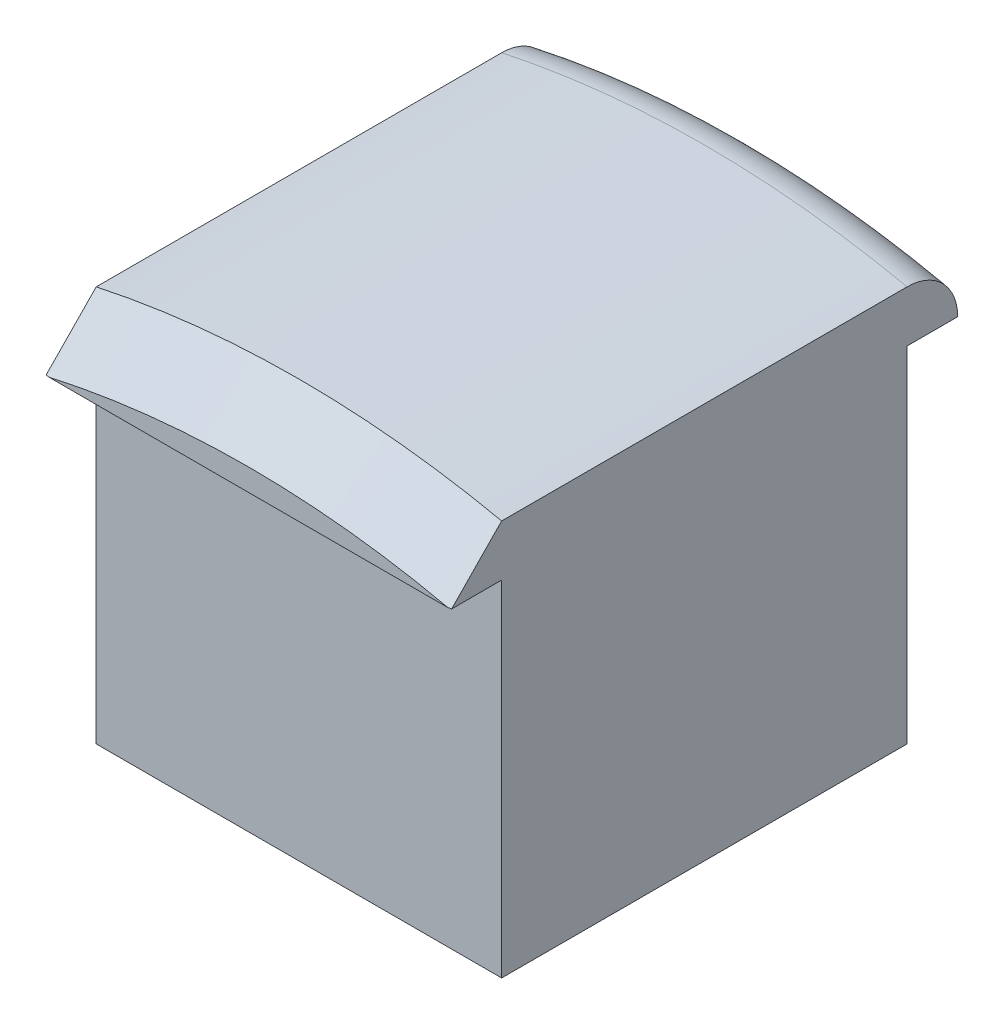
SolidWorks part; units mm, degrees
ref_plane "Alzado" through (0, 0, 0) normal (0, 0, 1) x (1, 0, 0)
ref_plane "Planta" through (0, 0, 0) normal (0, 1, 0) x (1, 0, 0)
ref_plane "Vista lateral" through (0, 0, 0) normal (1, 0, 0) x (0, 0, -1)
sketch "Croquis1" plane through (0, 0, 0) normal (0, 0, 1) x (1, 0, 0)
  line L9 (-50.7946, 110.0777) -> (-50.7946, 76.8462)
  line L10 (-50.7946, 76.8462) -> (-10.7946, 76.8462)
  line L11 (-10.7946, 76.8462) -> (-10.7946, 110.0777)
  line L14 (-50.7946, 110.0777) -> (-50.7946, 115.8971)
  line L15 (-10.7946, 110.0777) -> (-10.7946, 115.8971)
  arc A1 (-10.7946, 115.8971) -> (-50.7946, 115.8971) centre (-30.7946, 23.0262) ccw
  point P1 (-30.7946, 118.0262)
  dimension "D1" = 41.18
  dimension "D9" = 190
  dimension "D3" = 40
  dimension "D6" = 20
extrude "Saliente-Extruir1" add sketch "Croquis1" along normal blind 50
sketch "Croquis4" plane through (-50.7946, 0, 0) normal (-1, 0, 0) x (0, 0, 1)
  line L0 (0, 76.8462) -> (0, 115.8971) construction
  line L1 (0, 110.8462) -> (5, 110.8462)
  line L2 (0, 110.8462) -> (0, 76.8462)
  line L3 (0, 76.8462) -> (5, 76.8462)
  line L4 (5, 110.8462) -> (5, 76.8462)
  line L5 (50, 76.8462) -> (0, 76.8462) construction
  line L6 (50, 76.8462) -> (50, 115.8971) construction
  line L7 (50, 110.8462) -> (45, 110.8462)
  line L8 (50, 110.8462) -> (50, 76.8462)
  line L9 (50, 76.8462) -> (45, 76.8462)
  line L10 (45, 110.8462) -> (45, 76.8462)
  dimension "D1" = 5
  dimension "D2" = 5
  dimension "D3" = 34
  dimension "D4" = 34
extrude "Cortar-Extruir3" cut sketch "Croquis4" against normal blind 50
sketch "Croquis5" plane through (0, 0, 5) normal (0, 0, -1) x (-1, 0, 0)
  line L0 (10.7946, 110.8462) -> (50.7946, 110.8462) construction
  line L1 (12.7946, 110.8462) -> (48.7946, 110.8462)
  line L2 (12.7946, 110.8462) -> (12.7946, 78.8462)
  line L3 (12.7946, 78.8462) -> (48.7946, 78.8462)
  line L4 (48.7946, 110.8462) -> (48.7946, 78.8462)
  line L5 (10.7946, 76.8462) -> (10.7946, 110.8462) construction
  line L6 (50.7946, 76.8462) -> (50.7946, 110.8462) construction
  line L7 (10.7946, 76.8462) -> (50.7946, 76.8462) construction
  dimension "D1" = 2
  dimension "D2" = 2
  dimension "D3" = 2
extrude "Cortar-Extruir4" cut sketch "Croquis5" against normal blind 38
fillet "Redondeo1" radius 5 1 edges at (-30.7946, 118.0262, 0)
chamfer "Chaflán1" distance 5 angle 45 1 edges at (-30.7946, 118.0262, 50)
